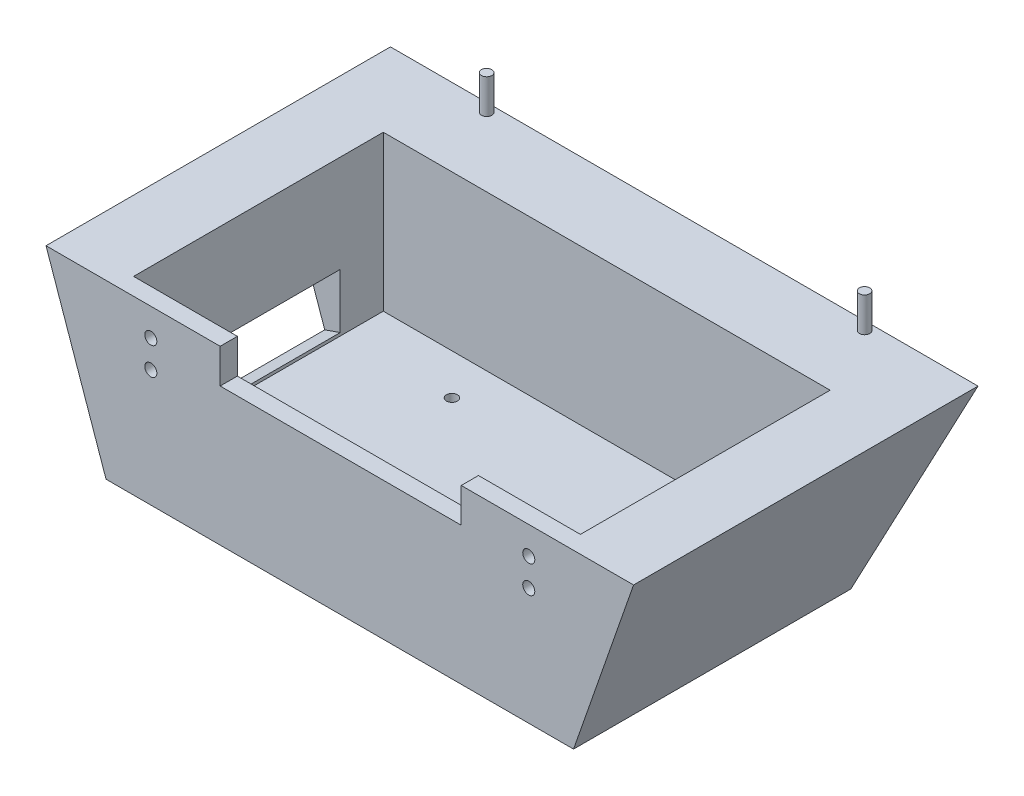
SolidWorks part; units mm, degrees
ref_plane "Front Plane" through (0, 0, 0) normal (0, 0, 1) x (1, 0, 0)
ref_plane "Top Plane" through (0, 0, 0) normal (0, 1, 0) x (1, 0, 0)
ref_plane "Right Plane" through (0, 0, 0) normal (1, 0, 0) x (0, 0, -1)
sketch "Sketch3" plane through (0, 0, 0) normal (0, 1, 0) x (1, 0, 0)
  line L1 (-78.8399, -20.4646) -> (56.8901, -20.4646)
  line L2 (-78.8399, -20.4646) -> (-78.8399, -100.9646)
  line L3 (-78.8399, -100.9646) -> (56.8901, -100.9646)
  line L4 (56.8901, -20.4646) -> (56.8901, -100.9646)
  point P4 (0, 0)
  point P5 (0, 0)
  point P6 (0, 0)
  point P7 (0, 0)
extrude "Boss-Extrude1" add sketch "Sketch3" along normal blind 5
sketch "Sketch4" plane through (0, 5, 0) normal (0, 1, 0) x (1, 0, 0)
  line L2 (-78.8399, -20.4646) -> (-78.8399, -100.9646) construction
  line L3 (56.8901, -100.9646) -> (-78.8399, -100.9646)
  line L4 (56.8901, -100.9646) -> (56.8901, -95.9646)
  line L6 (56.8901, -95.9646) -> (-78.8399, -95.9646)
  line L7 (-78.8399, -100.9646) -> (-78.8399, -95.9646)
  line L9 (56.8901, -20.4646) -> (51.8901, -20.4646)
  line L10 (56.8901, -20.4646) -> (56.8901, -100.9646)
  line L11 (56.8901, -100.9646) -> (51.8901, -100.9646)
  line L12 (51.8901, -20.4646) -> (51.8901, -100.9646)
  line L13 (-78.8399, -20.4646) -> (-73.8399, -20.4646)
  line L14 (-78.8399, -20.4646) -> (-78.8399, -100.9646)
  line L15 (-78.8399, -100.9646) -> (-73.8399, -100.9646)
  line L16 (-73.8399, -20.4646) -> (-73.8399, -100.9646)
  line L17 (-78.8399, -20.4646) -> (56.8901, -20.4646)
  line L18 (-78.8399, -20.4646) -> (-78.8399, -25.4646)
  line L19 (-78.8399, -25.4646) -> (56.8901, -25.4646)
  line L20 (56.8901, -20.4646) -> (56.8901, -25.4646)
  point P6 (0, 0)
  point P13 (0, 0)
  point P19 (0, 0)
  line M1 (-78.8399, -20.4646) -> (-78.8399, -100.9646)
  line M2 (-78.8399, -100.9646) -> (56.8901, -100.9646)
  line M3 (56.8901, -100.9646) -> (56.8901, -20.4646)
  line M4 (56.8901, -20.4646) -> (-78.8399, -20.4646)
extrude "Boss-Extrude2" add sketch "Sketch4" along normal blind 45 contours L12 L6 M4 M3 | L6 L16 L3 L12 | L16 L6 M4 M1 | L16 L6 M1 M2 | L6 L12 L3 M3 | L16 L19 L12 M4 | L19 L16 M1 M4 | L12 L19 L10 M4
sketch "Sketch8" plane through (0, 50, 0) normal (0, 1, 0) x (1, 0, 0)
  line L0 (24.2901, -95.9646) -> (24.2901, -100.9646) construction
  line L2 (24.2901, -100.9646) -> (24.2901, -95.9646)
  line L3 (-45.7099, -95.9646) -> (24.2901, -95.9646)
  line L4 (-45.7099, -95.9646) -> (-45.7099, -100.9646)
  line L6 (-45.7099, -95.9646) -> (-45.7099, -100.9646) construction
  line L7 (-45.7099, -100.9646) -> (24.2901, -100.9646)
  line L8 (-78.8399, -100.9646) -> (56.8901, -100.9646) construction
  line L11 (51.8901, -95.9646) -> (-73.8399, -95.9646) construction
  line L13 (24.2901, -95.9646) -> (24.2901, -100.9646) construction
extrude "Cut-Extrude2" cut sketch "Sketch8" against normal blind 10
draft "Draft3" type of draft neutral plane draft angle 21.306 faces to draft 1 face at (-10.9749, 25, 20.4646) neutral plane through (0, 0, 0) neutral plane normal (0, -1, 0) parameters "D1"=21.306
draft "Draft4" type of draft neutral plane draft angle 19.219 faces to draft 2 face at (-78.8399, 25, 55.8396) face at (56.8901, 25, 55.8396) neutral plane through (0, 0, 0) neutral plane normal (0, -1, 0) parameters "D1"=19.219
sketch "Sketch12" plane through (0, 0, 95.9646) normal (0, 0, -1) x (-1, 0, 0)
  line L0 (73.8399, 50) -> (53.7099, 50) construction
  line L2 (-51.8901, 50) -> (-43.8901, 50) construction
  line L3 (65.8399, 42) -> (65.8399, 34) construction
  line L5 (53.7099, 50) -> (65.8399, 42) construction
  line L6 (53.7099, 50) -> (45.7099, 50) construction
  line L8 (45.7099, 50) -> (73.8399, 50) construction
  line L9 (-43.8901, 50) -> (-43.8901, 5) construction
  line L10 (-51.8901, 5) -> (73.8399, 5) construction
  line L11 (-43.8901, 50) -> (-43.8901, 42) construction
  line L12 (-43.8901, 42) -> (-43.8901, 34) construction
  line L13 (-43.8901, 50) -> (-24.2901, 50) construction
  line L14 (-51.8901, 50) -> (-24.2901, 50) construction
  circle A0 centre (65.8399, 42) radius 1.75
  circle A1 centre (65.8399, 34) radius 1.75
  circle A2 centre (-43.8901, 42) radius 1.75
  circle A3 centre (-43.8901, 34) radius 1.75
  point P2 (0, 0)
  point P3 (0, 0)
extrude "Cut-Extrude3" cut sketch "Sketch12" against normal blind 10
sketch "Sketch15" plane through (0, 50, 0) normal (0, 1, 0) x (1, 0, 0)
  line L0 (-73.8399, -95.9646) -> (-75.8399, -95.9646)
  line L6 (-75.8399, -95.9646) -> (-75.8399, -50.577)
  line L7 (-75.8399, -50.577) -> (-75.8399, -23.4646)
  line L11 (51.8901, -25.4646) -> (51.8901, -95.9646) construction
  line L13 (40.2901, -23.4646) -> (53.8901, -23.4646) construction
  line L14 (53.8901, -23.4646) -> (53.8901, -95.9646) construction
  line L15 (53.8901, -95.9646) -> (51.8901, -95.9646) construction
  line L16 (-75.8399, -23.4646) -> (53.8901, -23.4646)
  line L17 (53.8901, -23.4646) -> (53.8901, -95.9646)
  line L18 (53.8901, -95.9646) -> (51.8901, -95.9646)
  line L19 (51.8901, -95.9646) -> (51.8901, -25.4646)
  line L20 (51.8901, -25.4646) -> (-73.8399, -25.4646)
  line L21 (-73.8399, -25.4646) -> (-73.8399, -95.9646)
  point P4 (0, 0)
  point P5 (0, 0)
  point P6 (0, 0)
extrude "Cut-Extrude4" cut sketch "Sketch15" against normal blind 45
sketch "Sketch19" plane through (0, 5, 0) normal (0, 1, 0) x (1, 0, 0)
  circle A0 centre (-45.3399, -83.562) radius 1.6
  circle A1 centre (-44.0699, -35.302) radius 1.6
  circle A2 centre (30.8601, -35.302) radius 1.6
  circle A3 centre (37.2101, -83.562) radius 1.6
extrude "Cut-Extrude5" cut sketch "Sketch19" against normal blind 10
sketch "Sketch20" plane through (-70.2973, -24.5056, 0) normal (-0.9443, -0.3292, 0) x (0, 0, 1)
  line L4 (85.9646, 30.5191) -> (85.9646, 45.5191)
  line L5 (85.9646, 45.5191) -> (35.9646, 45.5191)
  line L6 (35.9646, 45.5191) -> (35.9646, 30.5191)
  line L7 (35.9646, 30.5191) -> (85.9646, 30.5191)
extrude "Cut-Extrude6" cut sketch "Sketch20" against normal blind 15
sketch "Sketch21" plane through (0, 50, 0) normal (0, 1, 0) x (1, 0, 0)
  circle A0 centre (-65.8399, -3.4646) radius 1.5
  circle A1 centre (43.8901, -3.4646) radius 1.5
extrude "Boss-Extrude3" add sketch "Sketch21" along normal blind 10
